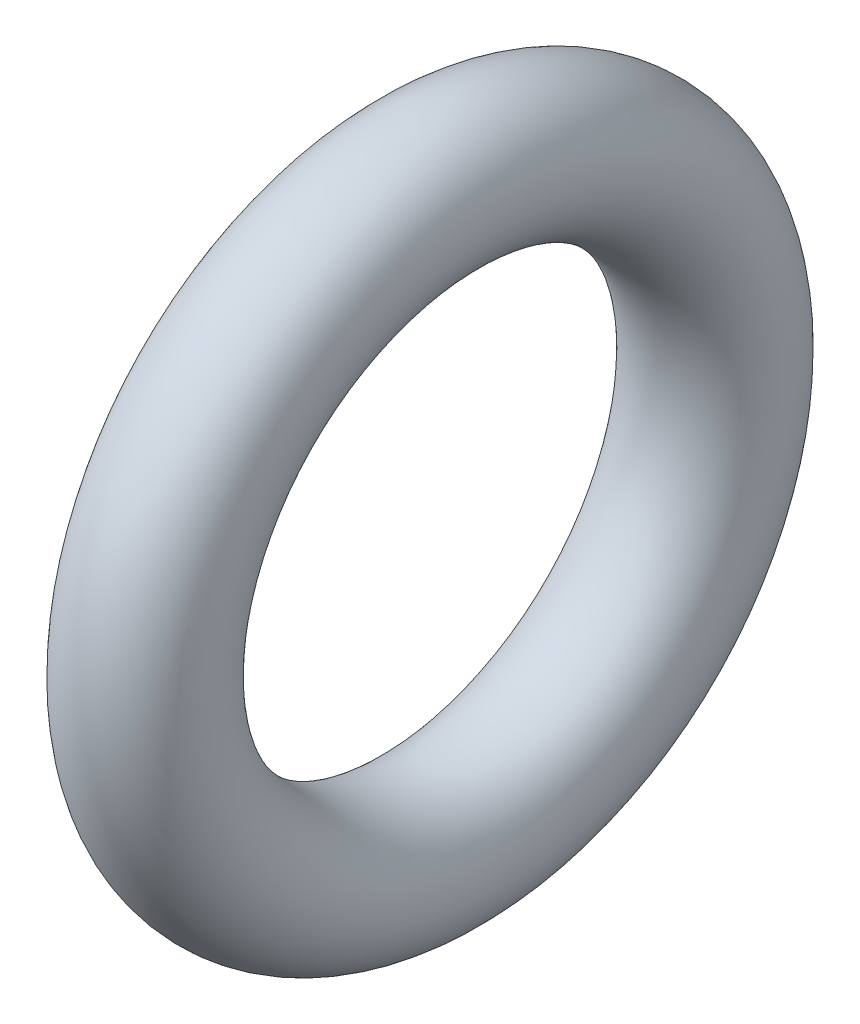
SolidWorks part; units mm, degrees
material "Guma"
ref_plane "Przednia" through (0, 0, 0) normal (0, 0, 1) x (1, 0, 0)
ref_plane "Górna" through (0, 0, 0) normal (0, 1, 0) x (1, 0, 0)
ref_plane "Prawa" through (0, 0, 0) normal (1, 0, 0) x (0, 0, -1)
sketch "Szkic3" plane through (0, 0, 0) normal (0, 0, 1) x (1, 0, 0)
  line L0 (-10.8914, 0) -> (15.9042, 0) construction
  line L1 (0, -5.0507) -> (0, 14.0717) construction
  circle A0 centre (0, 4.1) radius 1
  dimension "D1" = 2
  dimension "D2" = 4.1
revolve "Obrót1" add sketch "Szkic3" angle 360 about L0
